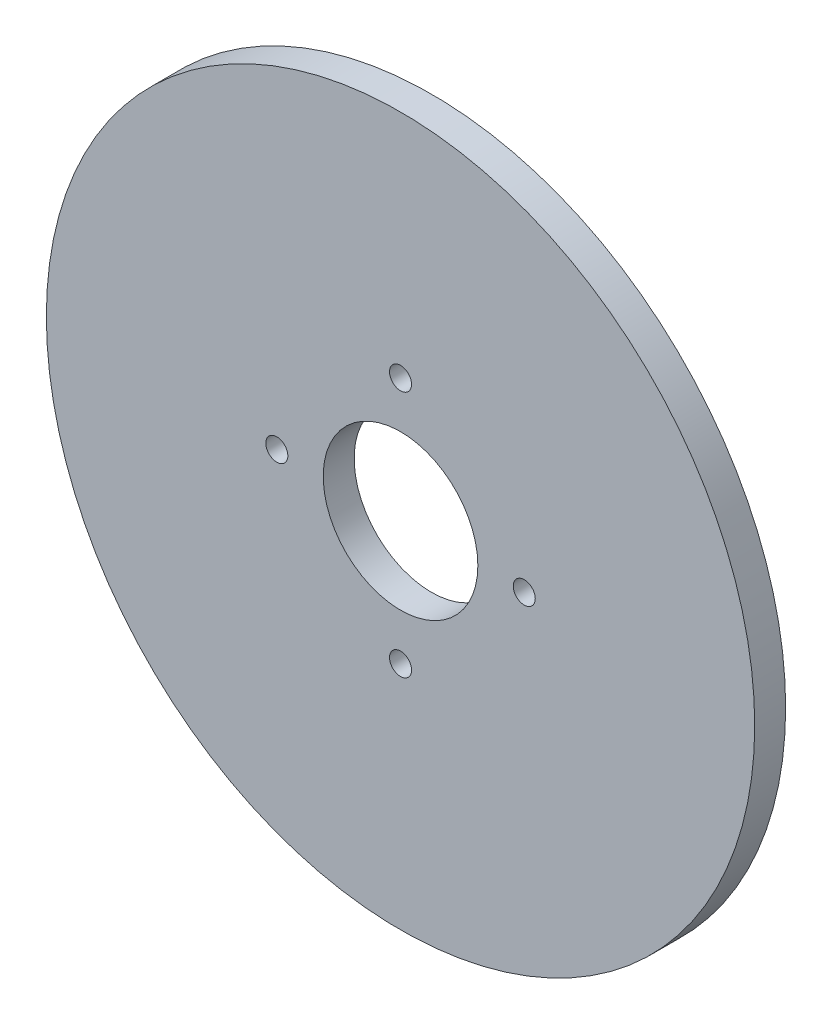
SolidWorks part; units mm, degrees
material "6061 Alloy"
ref_plane "Front Plane" through (0, 0, 0) normal (0, 0, 1) x (1, 0, 0)
ref_plane "Top Plane" through (0, 0, 0) normal (0, 1, 0) x (1, 0, 0)
ref_plane "Right Plane" through (0, 0, 0) normal (1, 0, 0) x (0, 0, -1)
sketch "Sketch1" plane through (0, 0, 0) normal (0, 0, 1) x (1, 0, 0)
  circle A0 centre (0, 0) radius 36.3601
  circle A1 centre (0, 0) radius 7.9375
  dimension "D1" = 72.7202
  dimension "D2" = 15.875
extrude "Boss-Extrude1" add sketch "Sketch1" along normal blind 3.175
hole_wizard "Tap Drill for #4-40 Tap1" positions "Sketch2" profile "Sketch3" hole size "#4-40" standard "ANSI Inch"
sketch "Sketch2" plane through (0, 0, 3.175) normal (0, 0, 1) x (1, 0, 0)
  point P0 (0, 12.7)
  point P2 (0, -12.7)
  point P4 (12.7, 0)
  point P6 (-12.7, 0)
  dimension "D1" = 12.7
  dimension "D2" = 12.7
  dimension "D3" = 12.7
  dimension "D4" = 12.7
sketch "Sketch3" plane through (0, 12.7, 3.175) normal (1, 0, 0) x (0, -1, 0)
  line L0 (0, 0) -> (0, 4.6792)
  line L1 (0, 4.6792) -> (1.1303, 4)
  line L2 (1.1303, 4) -> (1.1303, 0)
  line L5 (1.1303, 0) -> (0, 0)
  line L10 (0, 4.6792) -> (-1.1303, 4) construction
  line L11 (0, -6.35) -> (0, 107.95) construction
  dimension "Hole Dia." = 2.2606
  dimension "Hole Depth" = 4
  dimension "Drill Angle" = 118
